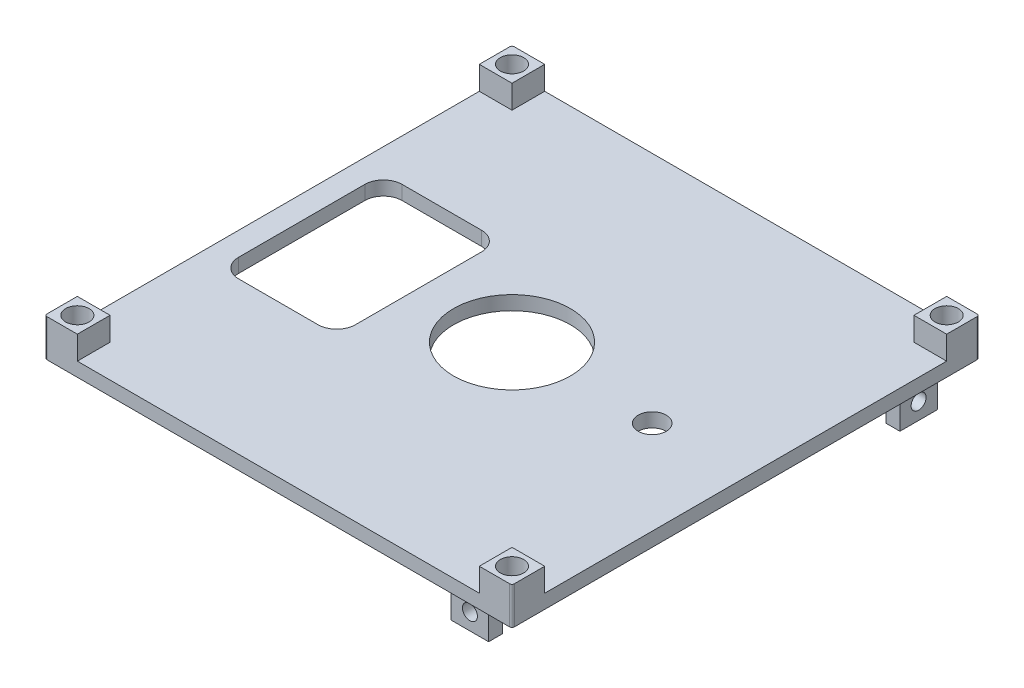
SolidWorks part; units mm, degrees
material "6061-T6 (SS)"
ref_plane "Front Plane" through (0, 0, 0) normal (0, 0, 1) x (1, 0, 0)
ref_plane "Top Plane" through (0, 0, 0) normal (0, 1, 0) x (1, 0, 0)
ref_plane "Right Plane" through (0, 0, 0) normal (1, 0, 0) x (0, 0, -1)
sketch "Sketch1" plane through (0, 0, 0) normal (0, 1, 0) x (1, 0, 0)
  line L0 (50, -50) -> (-50, -50) construction
  line L1 (50, -50) -> (50, 50) construction
  line L2 (50, 50) -> (-50, 50) construction
  line L3 (-50, -50) -> (-50, 50) construction
  line L4 (50, -50) -> (-50, 50) construction
  line L5 (50, 50) -> (-50, -50) construction
  line L6 (-50, 50) -> (-43, 50) construction
  line L7 (-50, 50) -> (-50, 43) construction
  line L8 (-50, 43) -> (-43, 43) construction
  line L9 (-43, 50) -> (-43, 43) construction
  line L10 (-50, -50) -> (-43, -50) construction
  line L11 (-50, -50) -> (-50, -43) construction
  line L12 (-50, -43) -> (-43, -43) construction
  line L13 (-43, -50) -> (-43, -43) construction
  line L14 (50, -50) -> (43, -50) construction
  line L15 (50, -50) -> (50, -43) construction
  line L16 (50, -43) -> (43, -43) construction
  line L17 (43, -50) -> (43, -43) construction
  line L18 (50, 50) -> (43, 50) construction
  line L19 (50, 50) -> (50, 43) construction
  line L20 (50, 43) -> (43, 43) construction
  line L21 (43, 50) -> (43, 43) construction
  line L22 (-32.625, 45.061) -> (33.923, 45.061) construction
  line L23 (-32.625, 45.061) -> (-32.625, 35.082) construction
  line L24 (-32.625, 35.082) -> (33.923, 35.082) construction
  line L25 (33.923, 45.061) -> (33.923, 35.082) construction
  line L26 (-50, 50) -> (-35, 50)
  line L27 (-50, 50) -> (-50, 48)
  line L28 (-50, 48) -> (-35, 48)
  line L29 (-35, 50) -> (-35, 48)
  line L30 (-50, 50) -> (-48, 50)
  line L31 (-50, 50) -> (-50, 35)
  line L32 (-50, 35) -> (-48, 35)
  line L33 (-48, 50) -> (-48, 35)
  line L34 (50, 50) -> (35, 50)
  line L35 (50, 50) -> (50, 48)
  line L36 (50, 48) -> (35, 48)
  line L37 (35, 50) -> (35, 48)
  line L38 (50, 50) -> (48, 50)
  line L39 (50, 50) -> (50, 35)
  line L40 (50, 35) -> (48, 35)
  line L41 (48, 50) -> (48, 35)
  line L42 (50, -50) -> (48, -50)
  line L43 (50, -50) -> (50, -35)
  line L44 (50, -35) -> (48, -35)
  line L45 (48, -50) -> (48, -35)
  line L46 (50, -50) -> (35, -50)
  line L47 (50, -50) -> (50, -48)
  line L48 (50, -48) -> (35, -48)
  line L49 (35, -50) -> (35, -48)
  line L50 (-50, -50) -> (-35, -50)
  line L51 (-50, -50) -> (-50, -48)
  line L52 (-50, -48) -> (-35, -48)
  line L53 (-35, -50) -> (-35, -48)
  line L54 (-50, -50) -> (-48, -50)
  line L55 (-50, -50) -> (-50, -35)
  line L56 (-50, -35) -> (-48, -35)
  line L57 (-48, -50) -> (-48, -35)
  circle A0 centre (-36.2, 42.85) radius 1.6
  circle A1 centre (37.5, 42.85) radius 1.6
  circle A2 centre (40, -42.85) radius 1.6
  circle A3 centre (-40, -42.85) radius 1.6
  point P0 (0, 0)
  point P5 (0, 0)
  point P6 (0, 0)
  dimension "D6" = 3.2
  dimension "D1" = 100
  dimension "D2" = 7
  dimension "D3" = 7
  dimension "D4" = 7
  dimension "D5" = 7
  dimension "D7" = 7.15
  dimension "D8" = 13.8
  dimension "D9" = 10
  dimension "D10" = 7.15
  dimension "D11" = 10
  dimension "D12" = 7.15
  dimension "D13" = 17.375
  dimension "D14" = 4.939
  dimension "D15" = 14.918
  dimension "D16" = 16.077
  dimension "D17" = 73.7
  dimension "D18" = 15
  dimension "D19" = 2
  dimension "D20" = 15
  dimension "D21" = 2
  dimension "D22" = 2
  dimension "D23" = 15
  dimension "D24" = 15
  dimension "D25" = 2
  dimension "D26" = 15
  dimension "D27" = 2
  dimension "D28" = 2
  dimension "D29" = 15
  dimension "D30" = 15
  dimension "D31" = 15
  dimension "D32" = 2
  dimension "D33" = 2
  dimension "D34" = 100
sketch "Sketch2" plane through (0, 0, 0) normal (0, 1, 0) x (1, 0, 0)
  line L0 (50, -50) -> (50, 50) construction
  line L1 (50, -50) -> (-50, -50) construction
  line L2 (-50, -50) -> (-50, 50) construction
  line L3 (50, 50) -> (-50, 50) construction
  line L4 (50, -50) -> (50, 50)
  line L5 (50, -50) -> (-50, -50)
  line L6 (-50, -50) -> (-50, 50)
  line L7 (50, 50) -> (-50, 50)
  circle A0 centre (0, 0) radius 12.5
  dimension "D1" = 25
extrude "Boss-Extrude1" add sketch "Sketch2" along normal blind 3
sketch "Sketch3" plane through (0, 3, 0) normal (0, 1, 0) x (1, 0, 0)
  line L0 (-50, 43) -> (-43, 43) construction
  line L1 (-50, 50) -> (-50, 43) construction
  line L2 (-43, 50) -> (-43, 43) construction
  line L3 (-50, 50) -> (-43, 50) construction
  line L4 (-50, 43) -> (-43, 43)
  line L5 (-50, 50) -> (-50, 43)
  line L6 (-43, 50) -> (-43, 43)
  line L7 (-50, 50) -> (-43, 50)
  line L8 (50, 43) -> (43, 43) construction
  line L9 (50, 50) -> (50, 43) construction
  line L10 (43, 50) -> (43, 43) construction
  line L11 (50, 50) -> (43, 50) construction
  line L12 (50, -43) -> (43, -43) construction
  line L13 (50, -50) -> (50, -43) construction
  line L14 (43, -50) -> (43, -43) construction
  line L15 (50, -50) -> (43, -50) construction
  line L16 (-50, -43) -> (-43, -43) construction
  line L17 (-50, -50) -> (-50, -43) construction
  line L18 (-43, -50) -> (-43, -43) construction
  line L19 (-50, -50) -> (-43, -50) construction
  line L20 (50, 43) -> (43, 43)
  line L21 (50, 50) -> (50, 43)
  line L22 (43, 50) -> (43, 43)
  line L23 (50, 50) -> (43, 50)
  line L24 (50, -43) -> (43, -43)
  line L25 (50, -50) -> (50, -43)
  line L26 (43, -50) -> (43, -43)
  line L27 (50, -50) -> (43, -50)
  line L28 (-50, -43) -> (-43, -43)
  line L29 (-50, -50) -> (-50, -43)
  line L30 (-43, -50) -> (-43, -43)
  line L31 (-50, -50) -> (-43, -50)
extrude "Boss-Extrude2" add sketch "Sketch3" along normal blind 5
sketch "Sketch4" plane through (0, 0, 0) normal (0, -1, 0) x (1, 0, 0)
  line L0 (-48, -50) -> (-48, -35) construction
  line L1 (-48, -43) -> (-45, -43)
  line L2 (-48, -43) -> (-48, -35)
  line L3 (-48, -35) -> (-45, -35)
  line L4 (-45, -43) -> (-45, -35)
  line L5 (-50, -43) -> (-43, -43) construction
  line L6 (43, -50) -> (43, -43) construction
  line L7 (35, -48) -> (43, -48)
  line L8 (35, -48) -> (35, -45)
  line L9 (35, -45) -> (43, -45)
  line L10 (43, -48) -> (43, -45)
  line L11 (50, -43) -> (43, -43) construction
  line L12 (48, -35) -> (45, -35)
  line L13 (48, -35) -> (48, -43)
  line L14 (48, -43) -> (45, -43)
  line L15 (45, -35) -> (45, -43)
  line L17 (35, 48) -> (43, 48)
  line L18 (35, 48) -> (35, 45)
  line L19 (35, 45) -> (43, 45)
  line L20 (43, 48) -> (43, 45)
  line L21 (50, 43) -> (43, 43) construction
  line L22 (48, 35) -> (45, 35)
  line L23 (48, 35) -> (48, 43)
  line L24 (48, 43) -> (45, 43)
  line L25 (45, 35) -> (45, 43)
  line L26 (-50, 43) -> (-43, 43) construction
  line L27 (-48, 35) -> (-45, 35)
  line L28 (-48, 35) -> (-48, 43)
  line L29 (-48, 43) -> (-45, 43)
  line L30 (-45, 35) -> (-45, 43)
  line L31 (-43, 50) -> (-43, 43) construction
  line L32 (-35, 48) -> (-43, 48)
  line L33 (-35, 48) -> (-35, 45)
  line L34 (-35, 45) -> (-43, 45)
  line L35 (-43, 48) -> (-43, 45)
  line L36 (43, 50) -> (43, 43) construction
  line L40 (-50, -48) -> (-35, -48) construction
  line L41 (-43, -48) -> (-35, -48)
  line L42 (-43, -48) -> (-43, -45)
  line L43 (-43, -45) -> (-35, -45)
  line L44 (-35, -48) -> (-35, -45)
  line L45 (-43, -50) -> (-43, -43) construction
  dimension "D1" = 3
extrude "Boss-Extrude3" add sketch "Sketch4" along normal blind 7 contours L42 L41 L44 L43 | L18 L17 L20 L19 | L28 L27 L30 L29 | L13 L12 L15 L14
sketch "Sketch11" plane through (0, 8, 0) normal (0, 1, 0) x (1, 0, 0)
  line L4 (-43, 50) -> (-50, 50) construction
  line L5 (-50, 50) -> (-50, 43) construction
  line L6 (43, 43) -> (50, 43) construction
  line L7 (-43, -50) -> (-43, -43) construction
  circle A0 centre (-46.5, 46.5) radius 2.5
  circle A1 centre (46.5, 46.5) radius 2.5
  circle A2 centre (46.5, -46.5) radius 2.5
  circle A3 centre (-46.5, -46.5) radius 2.5
  point P11 (-46.5, 50)
  point P14 (-50, 46.5)
  point P21 (46.5, 43)
  point P22 (-43, -46.5)
  dimension "D1" = 5
extrude "Cut-Extrude6" cut sketch "Sketch11" against normal through all
sketch "Sketch5" plane through (0, 0, 50) normal (0, 0, -1) x (-1, 0, 0)
  line L3 (43, -7) -> (35, -7) construction
  line L4 (-43, -7) -> (-43, 0) construction
  line L5 (-35, -7) -> (-43, -7) construction
  circle A0 centre (-39, -3.5) radius 1.6
  circle A1 centre (39, -3.5) radius 1.6
  point P7 (-43, -3.5)
  point P12 (39, -7)
  point P13 (-39, -7)
  dimension "D1" = 3.2
  dimension "D2" = 3.2
extrude "Cut-Extrude1" cut sketch "Sketch5" along normal through all
sketch "Sketch6" plane through (0, 0, 0) normal (0, -1, 0) x (1, 0, 0)
  circle A0 centre (-40, 42.85) radius 1.6 construction
  circle A1 centre (40, 42.85) radius 1.6 construction
  circle A2 centre (-36.2, -42.85) radius 1.6 construction
  circle A3 centre (37.5, -42.85) radius 1.6 construction
  circle A4 centre (-40, 42.85) radius 1.6
  circle A5 centre (40, 42.85) radius 1.6
  circle A6 centre (-36.2, -42.85) radius 1.6
  circle A7 centre (37.5, -42.85) radius 1.6
extrude "Cut-Extrude2" [suppressed] cut sketch "Sketch6" against normal blind 0.1
sketch "Sketch7" plane through (0, 0, 0) normal (0, -1, 0) x (1, 0, 0)
  line L0 (50, 50) -> (50, -50) construction
  circle A0 centre (30, 0) radius 3
  point P4 (50, 0)
  dimension "D1" = 6
  dimension "D2" = 20
extrude "Cut-Extrude3" cut sketch "Sketch7" against normal blind 10
sketch "Sketch8" plane through (48, 0, 0) normal (1, 0, 0) x (0, 0, -1)
  line L0 (43, -7) -> (43, 0) construction
  line L1 (35, -7) -> (43, -7) construction
  line L2 (-35, -7) -> (-35, 0) construction
  line L3 (-35, -7) -> (-43, -7) construction
  circle A0 centre (39, -3.5) radius 1.6
  circle A1 centre (-39, -3.5) radius 1.5
  point P4 (43, -3.5)
  point P7 (39, -7)
  point P12 (-35, -3.5)
  point P15 (-39, -7)
  dimension "D1" = 3.2
  dimension "D2" = 3
extrude "Cut-Extrude4" cut sketch "Sketch8" against normal through all
fillet "Fillet1" radius 0.5 4 edges at (50, 4, 50) (-50, 4, 50) (-50, 4, -50) (50, 4, -50)
sketch "Sketch9" plane through (0, 3, 0) normal (0, 1, 0) x (1, 0, 0)
  line L0 (-50, 43) -> (-50, -43) construction
  line L1 (-41, 17.5) -> (-24, 17.5)
  line L2 (-45, 13.5) -> (-45, -13.5)
  line L3 (-41, -17.5) -> (-24, -17.5)
  line L4 (-20, 13.5) -> (-20, -13.5)
  arc A0 (-45, -13.5) -> (-41, -17.5) centre (-41, -13.5) ccw
  arc A1 (-24, -17.5) -> (-20, -13.5) centre (-24, -13.5) ccw
  arc A2 (-20, 13.5) -> (-24, 17.5) centre (-24, 13.5) ccw
  arc A3 (-41, 17.5) -> (-45, 13.5) centre (-41, 13.5) ccw
  point P12 (-32.5, 17.5)
  point P15 (-45, 0)
  point P16 (-50, 0)
  dimension "D1" = 4
  dimension "D2" = 35
  dimension "D3" = 25
  dimension "D4" = 5
extrude "Cut-Extrude5" cut sketch "Sketch9" against normal blind 10
